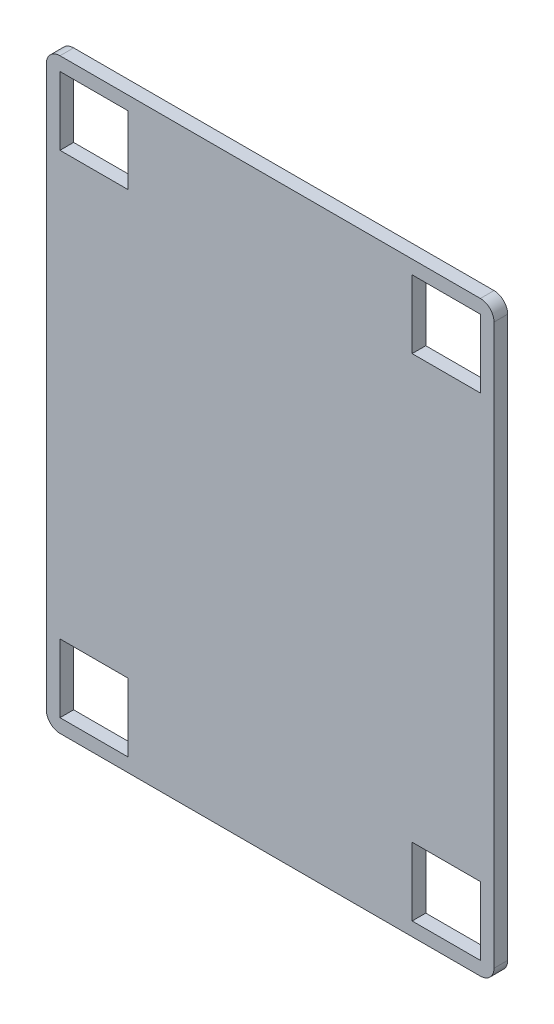
SolidWorks part; units mm, degrees
ref_plane "Plan de face" through (0, 0, 0) normal (0, 0, 1) x (1, 0, 0)
ref_plane "Plan de dessus" through (0, 0, 0) normal (0, 1, 0) x (1, 0, 0)
ref_plane "Plan de droite" through (0, 0, 0) normal (1, 0, 0) x (0, 0, -1)
sketch "Esquisse1" plane through (0, 0, 0) normal (0, 0, 1) x (1, 0, 0)
  line L0 (-82, 107.5) -> (82, 107.5)
  line L1 (82, 107.5) -> (82, -107.5)
  line L2 (82, -107.5) -> (-82, -107.5)
  line L3 (-82, -107.5) -> (-82, 107.5)
  line L4 (82, 107.5) -> (-82, -107.5) construction
  line L5 (-82, 107.5) -> (82, -107.5) construction
  point P2 (0, 0)
  dimension "D1" = 164
  dimension "D2" = 215
extrude "Boss.-Extru.1" add sketch "Esquisse1" along normal blind 5
sketch "Esquisse2" plane through (0, 0, 0) normal (0, 0, 1) x (1, 0, 0)
  line L0 (0, 107.5) -> (0, -107.5) construction
  line L1 (82, 107.5) -> (-82, 107.5) construction
  line L2 (-82, -107.5) -> (82, -107.5) construction
  line L3 (82, 0) -> (-82, 0) construction
  line L4 (82, -107.5) -> (82, 107.5) construction
  line L5 (-82, 107.5) -> (-82, -107.5) construction
  line L6 (-77, 102.5) -> (-52, 102.5)
  line L7 (-52, 102.5) -> (-52, 77.5)
  line L8 (-52, 77.5) -> (-77, 77.5)
  line L9 (-77, 77.5) -> (-77, 102.5)
  line L10 (52, 77.5) -> (77, 77.5)
  line L11 (77, 77.5) -> (77, 102.5)
  line L12 (77, 102.5) -> (52, 102.5)
  line L13 (52, 102.5) -> (52, 77.5)
  line L14 (52, -77.5) -> (77, -77.5)
  line L15 (77, -77.5) -> (77, -102.5)
  line L16 (52, -102.5) -> (52, -77.5)
  line L17 (77, -102.5) -> (52, -102.5)
  line L18 (-52, -102.5) -> (-52, -77.5)
  line L19 (-52, -77.5) -> (-77, -77.5)
  line L20 (-77, -77.5) -> (-77, -102.5)
  line L21 (-77, -102.5) -> (-52, -102.5)
  dimension "D1" = 25
  dimension "D2" = 25
  dimension "D3" = 5
  dimension "D4" = 5
extrude "Enlèv. mat.-Extru.1" cut sketch "Esquisse2" along normal blind 5
fillet "Congé1" radius 5 4 edges at (-82, -107.5, 2.5) (82, -107.5, 2.5) (82, 107.5, 2.5) (-82, 107.5, 2.5)
